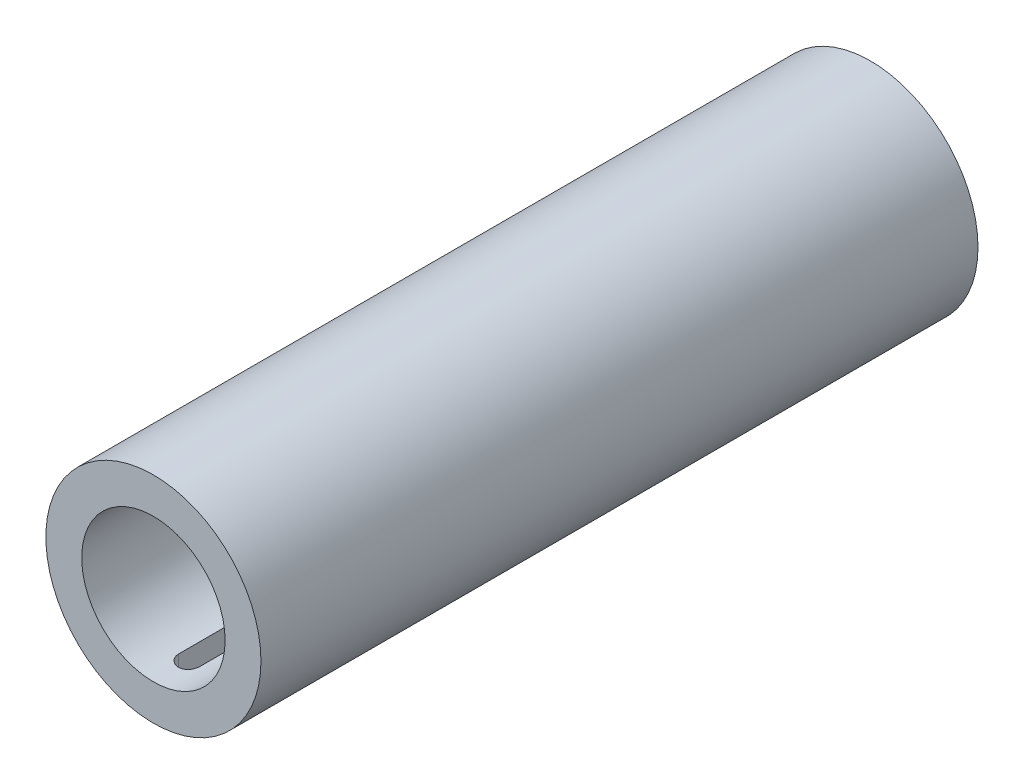
SolidWorks part; units mm, degrees
ref_plane "Front Plane" through (0, 0, 0) normal (1, 0, 0) x (0, 1, 0)
ref_plane "Top Plane" through (0, 0, 0) normal (0, 0, 1) x (0, 1, 0)
ref_plane "Right Plane" through (0, 0, 0) normal (0, 1, 0) x (-1, 0, 0)
sketch "Sketch1" plane through (0, 0, 0) normal (0, 0, 1) x (0, 1, 0)
  circle A0 centre (0, 0) radius 15
  circle A1 centre (0, 0) radius 10
  dimension "D1" = 30
  dimension "D2" = 20
extrude "Boss-Extrude1" add sketch "Sketch1" along normal blind 100
sketch "Sketch2" plane through (0, 0, 0) normal (0, 0, -1) x (-1, 0, 0)
  line L0 (0, -13.7326) -> (-1.5777, -11)
  line L1 (-1.5777, -11) -> (1.5777, -11)
  line L2 (1.5777, -11) -> (0, -13.7326)
  dimension "D1" = 11
extrude "Cut-Extrude1" cut sketch "Sketch2" against normal blind 1
sketch "Sketch4" plane through (0, 0, 0) normal (0, 1, 0) x (-1, 0, 0)
  line L0 (0, 20) -> (0, 95) construction
  line L1 (-1.5, 20) -> (-1.5, 95)
  line L2 (1.5, 20) -> (1.5, 95)
  line L3 (10, 100) -> (-10, 100) construction
  line L4 (-15, 0) -> (15, 0) construction
  arc A0 (-1.5, 20) -> (1.5, 20) centre (0, 20) ccw
  arc A1 (1.5, 95) -> (-1.5, 95) centre (0, 95) ccw
  point P3 (0, 57.5)
  dimension "D1" = 3
  dimension "D2" = 5
  dimension "D3" = 20
extrude "Cut-Extrude2" cut sketch "Sketch4" against normal through all
